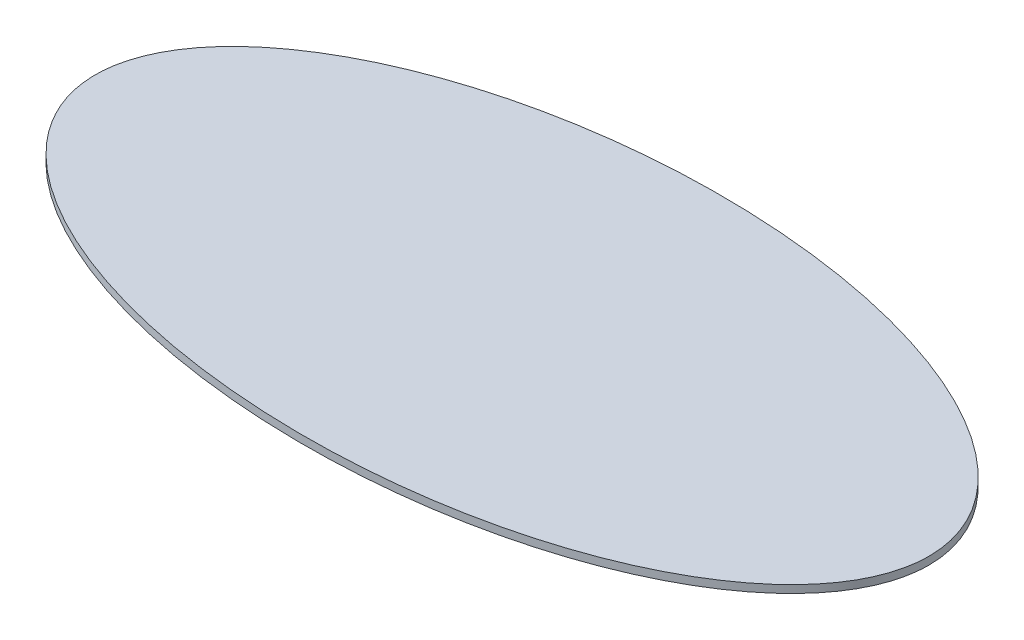
SolidWorks part; units mm, degrees
ref_plane "前视基准面" through (0, 0, 0) normal (0, 0, 1) x (1, 0, 0)
ref_plane "上视基准面" through (0, 0, 0) normal (0, 1, 0) x (1, 0, 0)
ref_plane "右视基准面" through (0, 0, 0) normal (1, 0, 0) x (0, 0, -1)
sketch "草图1" plane through (0, 0, 0) normal (0, 1, 0) x (1, 0, 0)
  line L0 (-53.8394, 0) -> (53.8394, 0) construction
  ellipse E0 centre (0, 0) end of major axis (54, 0) minor radius 27
extrude "凸台-拉伸1" add sketch "草图1" along normal blind 1
sketch "草图2" plane through (0, 1, 0) normal (0, 1, 0) x (1, 0, 0)
  line L0 (-54, 0) -> (54, 0) construction
  line L1 (0, 27) -> (0, -27) construction
  line L2 (-50, 0) -> (-46.9876, -7.8627)
  line L3 (-46.9876, -7.8627) -> (-40.6165, -13.4135)
  line L4 (-40.6165, -13.4135) -> (-33.085, -17.2447)
  line L5 (-33.085, -17.2447) -> (-25.0635, -19.9017)
  line L6 (-25.0635, -19.9017) -> (-16.7991, -21.663)
  line L7 (-16.7991, -21.663) -> (-8.4096, -22.6723)
  line L8 (-8.4096, -22.6723) -> (0, -23)
  line L9 (0.0104, -23) -> (0, -23)
  line L11 (-57, 40) -> (57, 40)
  line L12 (-57, 40) -> (-57, -40)
  line L13 (-57, -40) -> (57, -40)
  line L14 (57, 40) -> (57, -40)
  line L15 (-57, 40) -> (57, -40) construction
  line L16 (-57, -40) -> (57, 40) construction
  circle A0 centre (-50, 0) radius 0.5
  circle A1 centre (-46.9876, -7.8627) radius 0.5
  circle A2 centre (-40.6165, -13.4135) radius 0.5
  circle A3 centre (-33.085, -17.2447) radius 0.5
  circle A4 centre (-25.0635, -19.9017) radius 0.5
  circle A5 centre (-16.7991, -21.663) radius 0.5
  circle A6 centre (-8.4096, -22.6723) radius 0.5
  circle A7 centre (0, -23) radius 0.5
  circle A8 centre (0, 23) radius 0.5
  circle A9 centre (-8.4096, 22.6723) radius 0.5
  circle A10 centre (-16.7991, 21.663) radius 0.5
  circle A11 centre (-25.0635, 19.9017) radius 0.5
  circle A12 centre (-33.085, 17.2447) radius 0.5
  circle A13 centre (-40.6165, 13.4135) radius 0.5
  circle A14 centre (-46.9876, 7.8627) radius 0.5
  circle A15 centre (8.4096, -22.6723) radius 0.5
  circle A16 centre (16.7991, -21.663) radius 0.5
  circle A17 centre (25.0635, -19.9017) radius 0.5
  circle A18 centre (33.085, -17.2447) radius 0.5
  circle A19 centre (40.6165, -13.4135) radius 0.5
  circle A20 centre (46.9876, -7.8627) radius 0.5
  circle A21 centre (50, 0) radius 0.5
  circle A22 centre (46.9876, 7.8627) radius 0.5
  circle A23 centre (40.6165, 13.4135) radius 0.5
  circle A24 centre (33.085, 17.2447) radius 0.5
  circle A25 centre (25.0635, 19.9017) radius 0.5
  circle A26 centre (16.7991, 21.663) radius 0.5
  circle A27 centre (8.4096, 22.6723) radius 0.5
  ellipse E0 centre (0, 0) end of major axis (50, 0) minor radius 23 construction
  ellipse E2 centre (0, 0) end of major axis (54, 0) minor radius 27 construction
  dimension "D8" = 1
  dimension "D9" = 1
  dimension "D10" = 1
  dimension "D11" = 1
  dimension "D12" = 1
  dimension "D13" = 1
  dimension "D14" = 1
  dimension "D15" = 1
  dimension "D1" = 8.42
  dimension "D2" = 8.45
  dimension "D3" = 8.45
  dimension "D4" = 8.45
  dimension "D5" = 8.45
  dimension "D6" = 8.45
  dimension "D7" = 8.4096
  dimension "D16" = 54
  dimension "D17" = 108
  dimension "D18" = 80
  dimension "D19" = 57
